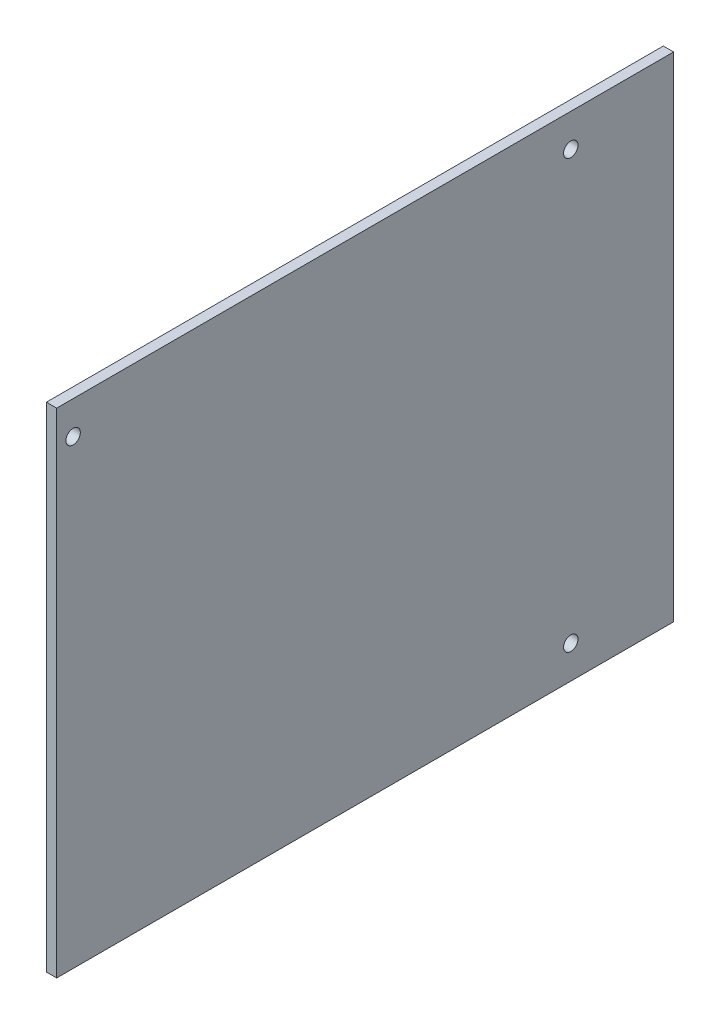
SolidWorks part; units mm, degrees
ref_plane "Front Plane" through (0, 0, 0) normal (0, 0, 1) x (1, 0, 0)
ref_plane "Top Plane" through (0, 0, 0) normal (0, 1, 0) x (1, 0, 0)
ref_plane "Right Plane" through (0, 0, 0) normal (1, 0, 0) x (0, 0, -1)
sketch "Sketch1" plane through (0, 0, 0) normal (1, 0, 0) x (0, 0, -1)
  line L0 (-132.288, 0) -> (225.2965, 0) construction
  line L1 (-75, -60) -> (75, -60)
  line L2 (-75, -60) -> (-75, 60)
  line L3 (-75, 60) -> (75, 60)
  line L4 (75, -60) -> (75, 60)
  line L5 (-75, -60) -> (75, 60) construction
  line L6 (-75, 60) -> (75, -60) construction
  circle A0 centre (50, 52) radius 1.75
  circle A1 centre (-71, 52) radius 1.75
  circle A2 centre (50, -52) radius 1.75
  point P0 (0, 0)
  point P10 (0, 0)
  dimension "D3" = 3.5
  dimension "D6" = 4
  dimension "D1" = 120
  dimension "D2" = 150
  dimension "D4" = 25
  dimension "D5" = 8
extrude "Boss-Extrude1" add sketch "Sketch1" along normal blind 2.5
